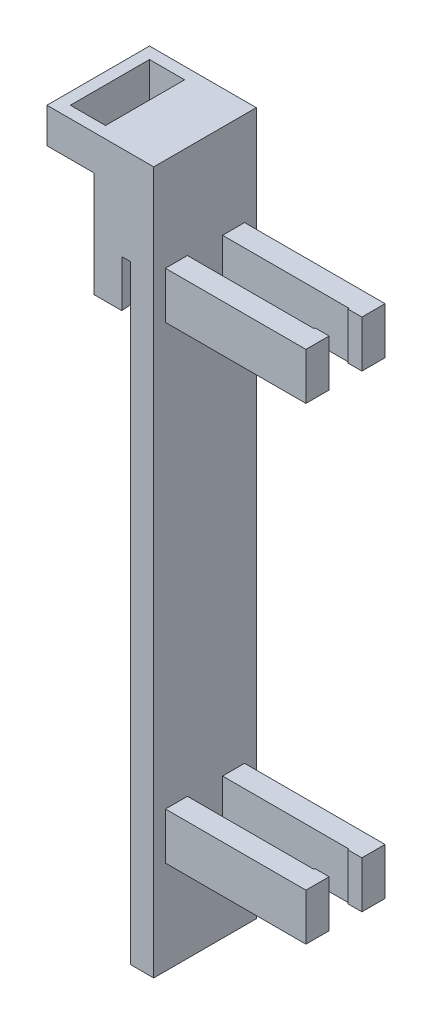
SolidWorks part; units mm, degrees
ref_plane "Front Plane" through (0, 0, 0) normal (0, 0, 1) x (1, 0, 0)
ref_plane "Top Plane" through (0, 0, 0) normal (0, 1, 0) x (1, 0, 0)
ref_plane "Right Plane" through (0, 0, 0) normal (1, 0, 0) x (0, 0, -1)
sketch "Sketch1" plane through (0, 0, 0) normal (0, 0, 1) x (1, 0, 0)
  line L0 (0, 0) -> (0, 30)
  line L1 (0, 30) -> (12.8, 30)
  line L2 (12.8, 30) -> (12.8, 0)
  line L3 (12.8, 0) -> (7.8, 0)
  line L4 (7.8, 0) -> (7.8, 10)
  line L5 (7.8, 10) -> (6, 10)
  line L6 (6, 10) -> (6, 0)
  line L7 (6, 0) -> (0, 0)
  dimension "D1" = 1.8
  dimension "D2" = 6
  dimension "D3" = 5
  dimension "D4" = 30
  dimension "D5" = 10
extrude "Boss-Extrude1" add sketch "Sketch1" along normal blind 21.9
sketch "Sketch2" plane through (12.8, 0, 0) normal (1, 0, 0) x (0, 0, -1)
  line L0 (-21.9, 0) -> (-21.9, 30) construction
  line L1 (-19.4, 10) -> (-14.7, 10)
  line L2 (-19.4, 10) -> (-19.4, 0)
  line L3 (-19.4, 0) -> (-14.7, 0)
  line L4 (-14.7, 10) -> (-14.7, 0)
  line L5 (-7.2, 10) -> (-2.5, 10)
  line L6 (-7.2, 10) -> (-7.2, 0)
  line L7 (-7.2, 0) -> (-2.5, 0)
  line L8 (-2.5, 10) -> (-2.5, 0)
  line L17 (-21.9, 0) -> (0, 0) construction
  dimension "D1" = 4.7
  dimension "D2" = 10
  dimension "D3" = 7.5
  dimension "D5" = 2.5
  dimension "D6" = 0
extrude "Boss-Extrude2" add sketch "Sketch2" along normal blind 30
sketch "Sketch3" plane through (0, 0, 0) normal (0, -1, 0) x (1, 0, 0)
  line L0 (7.8, 21.9) -> (12.8, 21.9)
  line L1 (12.8, 21.9) -> (12.8, 0)
  line L2 (12.8, 0) -> (7.8, 0)
  line L3 (7.8, 0) -> (7.8, 21.9)
extrude "Boss-Extrude3" add sketch "Sketch3" along normal blind 120
sketch "Sketch4" plane through (0, 0, 14.7) normal (0, 0, -1) x (-1, 0, 0)
  line L0 (-42.8, 10) -> (-39.8, 10)
  line L1 (-42.8, 10) -> (-12.8, 10) construction
  line L2 (-39.8, 10) -> (-39.8, 0)
  line L3 (-42.8, 0) -> (-12.8, 0) construction
  line L4 (-39.8, 0) -> (-42.8, 0)
  line L5 (-42.8, 0) -> (-42.8, 10)
  dimension "D1" = 3
extrude "Boss-Extrude4" add sketch "Sketch4" along normal blind 0.25
sketch "Sketch5" plane through (0, 0, 7.2) normal (0, 0, 1) x (1, 0, 0)
  line L0 (42.8, 10) -> (39.8, 10)
  line L1 (42.8, 10) -> (12.8, 10) construction
  line L2 (39.8, 10) -> (39.8, 0)
  line L3 (42.8, 0) -> (12.8, 0) construction
  line L4 (39.8, 0) -> (42.8, 0)
  line L5 (42.8, 0) -> (42.8, 10)
  dimension "D1" = 3
extrude "Boss-Extrude5" add sketch "Sketch5" along normal blind 0.25
sketch "Esboço2" plane through (0, 0, 0) normal (0, -1, 0) x (1, 0, 0)
  line L0 (6, 21.9) -> (6, 0)
  arc A0 (6, 21.9) -> (6, 0) centre (101.9774, 10.95) ccw
  dimension "D1" = 96.6
extrude "Corte-extrusão1" cut sketch "Esboço2" against normal blind 10
sketch "Esboço3" plane through (0, 0, 0) normal (-1, 0, 0) x (0, 0, 1)
  line L0 (21.9, 30) -> (21.9, 0) construction
  line L1 (0, 30) -> (21.9, 30)
  line L2 (0, 30) -> (0, 22.5)
  line L3 (0, 22.5) -> (21.9, 22.5)
  line L4 (21.9, 30) -> (21.9, 22.5)
  dimension "D1" = 7.5
extrude "Ressalto-extrusão2" add sketch "Esboço3" along normal blind 10
sketch "Esboço4" plane through (0, 22.5, 0) normal (0, -1, 0) x (1, 0, 0)
  line L0 (0, 0) -> (0, 21.9) construction
  line L1 (0, 19.4) -> (-7.5, 19.4)
  line L2 (0, 19.4) -> (0, 2.5)
  line L3 (0, 2.5) -> (-7.5, 2.5)
  line L4 (-7.5, 19.4) -> (-7.5, 2.5)
  line L5 (-10, 21.9) -> (0, 21.9) construction
  line L6 (-10, 0) -> (0, 0) construction
  dimension "D1" = 7.5
  dimension "D2" = 2.5
  dimension "D3" = 2.5
extrude "Corte-extrusão2" cut sketch "Esboço4" against normal blind 10
pattern_linear "Padrão linear1" count 2 spacing 100 along (0, -1, 0) of "Boss-Extrude2", "Boss-Extrude4", "Boss-Extrude5"
